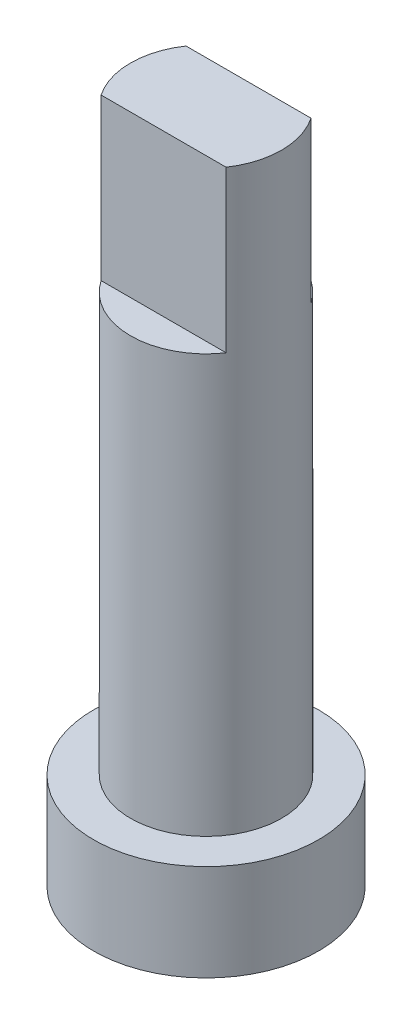
SolidWorks part; units mm, degrees
ref_plane "정면" through (0, 0, 0) normal (0, 0, 1) x (1, 0, 0)
ref_plane "윗면" through (0, 0, 0) normal (0, 1, 0) x (1, 0, 0)
ref_plane "우측면" through (0, 0, 0) normal (1, 0, 0) x (0, 0, -1)
sketch "스케치1" plane through (0, 0, 0) normal (0, 1, 0) x (1, 0, 0)
  circle A0 centre (0, 0) radius 2.35
  dimension "D1" = 4.7
extrude "보스-돌출1" add sketch "스케치1" along normal blind 18
ref_plane "평면1" through (0, 18, 0) normal (0, 1, 0) x (1, 0, 0)
sketch "스케치2" plane through (0, 18, 0) normal (0, 1, 0) x (1, 0, 0)
  line L1 (-2.0036, 1.2339) -> (1.9964, 1.2339)
  line L2 (-2.0036, 1.2339) -> (-2.0036, 2.4671)
  line L3 (-2.0036, 2.4671) -> (1.9964, 2.4671)
  line L4 (1.9964, 1.2339) -> (1.9964, 2.4671)
  line L6 (-2.0036, -1.2339) -> (1.9964, -1.2339)
  line L8 (1.9964, -1.2339) -> (1.9964, -2.4383)
  line L9 (1.9964, -2.4383) -> (-2.0036, -2.4383)
  line L10 (-2.0036, -1.2339) -> (-2.0036, -2.4383)
  point P16 (-0.0036, 1.2339)
  dimension "D3" = 4
ref_plane "평면2" through (0, 0, 0) normal (0, -1, 0) x (-1, 0, 0)
sketch "스케치3" plane through (0, 0, 0) normal (0, -1, 0) x (-1, 0, 0)
  circle A0 centre (0, 0) radius 3.5
  dimension "D1" = 7
extrude "보스-돌출2" add sketch "스케치3" along normal blind 3
ref_plane "평면3" through (0, 18, 0) normal (0, 1, 0) x (1, 0, 0)
sketch "스케치6" plane through (0, 18, 0) normal (0, 1, 0) x (1, 0, 0)
  line L0 (-2.0036, 1.2339) -> (-2.0036, 2.4671) construction
  line L1 (1.9964, 1.2339) -> (1.9964, 2.4671) construction
  line L2 (1.9964, 1.3206) -> (-1.9968, 1.3206)
  line L3 (-1.9968, 1.3206) -> (-2.0036, 2.4671)
  line L4 (-2.0036, 2.4671) -> (1.9964, 2.4671)
  line L5 (1.9964, 2.4671) -> (1.9964, 1.3206)
  line L6 (-3.5, 0) -> (3.5, 0) construction
  line L7 (1.9964, -2.4671) -> (1.9964, -1.3206)
  line L8 (-2.0036, -2.4671) -> (1.9964, -2.4671)
  line L9 (-1.9968, -1.3206) -> (-2.0036, -2.4671)
  line L10 (1.9964, -1.3206) -> (-1.9968, -1.3206)
  circle A0 centre (0, 0) radius 3.5 construction
  point P0 (-2.0036, 1.3053)
  point P1 (1.9964, 1.3206)
  point P4 (-1.9968, 1.3206)
extrude "컷-돌출2" cut sketch "스케치6" against normal blind 5
